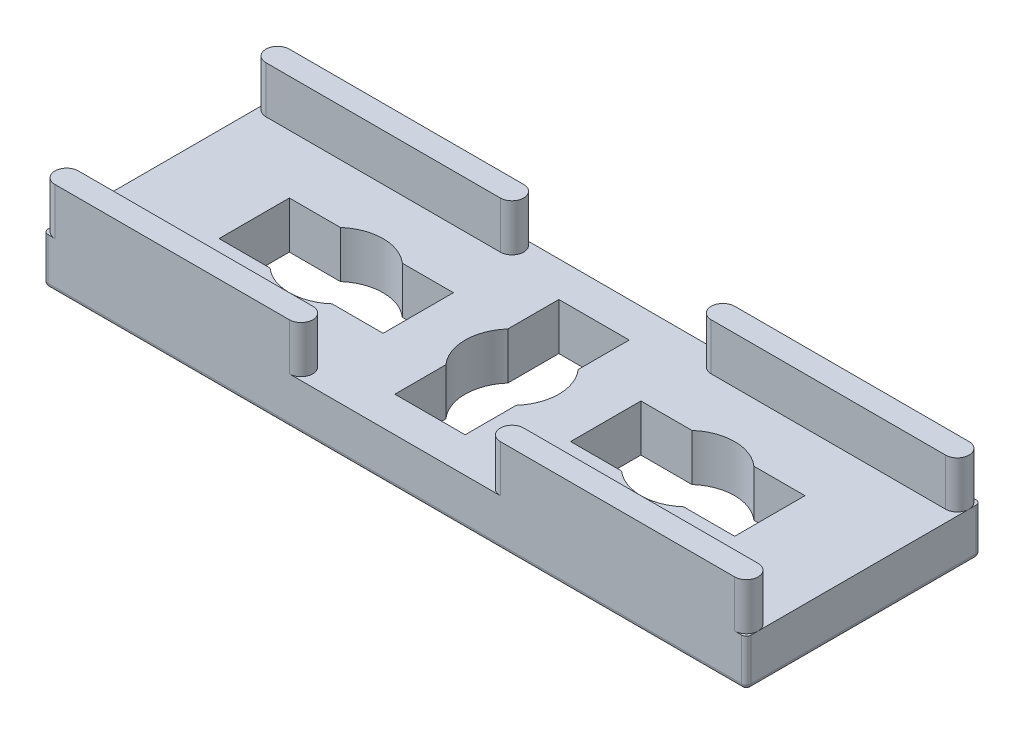
SolidWorks part; units mm, degrees
ref_plane "前视基准面" through (0, 0, 0) normal (0, 0, 1) x (1, 0, 0)
ref_plane "上视基准面" through (0, 0, 0) normal (0, 1, 0) x (1, 0, 0)
ref_plane "右视基准面" through (0, 0, 0) normal (1, 0, 0) x (0, 0, -1)
sketch "草图1" plane through (0, 0, 0) normal (0, 1, 0) x (1, 0, 0)
  line L0 (15, 5) -> (15, -5)
  line L1 (15, 5) -> (-15, 5)
  line L2 (15, -5) -> (-15, -5)
  line L3 (-15, 5) -> (-15, -5)
  line L4 (15, 5) -> (-15, -5) construction
  line L5 (15, -5) -> (-15, 5) construction
  point P1 (0, 0)
  dimension "D1" = 10
  dimension "D2" = 30
extrude "凸台-拉伸1" add sketch "草图1" along normal blind 2
sketch "草图2" plane through (0, 2, 0) normal (0, 1, 0) x (1, 0, 0)
  line L0 (-15, 5) -> (-14.5, 5) construction
  line L1 (15, 5) -> (-15, 5) construction
  line L2 (-14.5, 5) -> (-14.5, 4.5) construction
  line L3 (-14.5, 4.5) -> (-4.5, 4.5) construction
  line L4 (-14.5, 4) -> (-4.5, 4)
  line L5 (-14.5, 5) -> (-4.5, 5)
  arc A0 (-14.5, 5) -> (-14.5, 4) centre (-14.5, 4.5) ccw
  arc A1 (-4.5, 4) -> (-4.5, 5) centre (-4.5, 4.5) ccw
  dimension "D4" = 1
  dimension "D1" = 0.5
  dimension "D2" = 0.5
  dimension "D3" = 10
extrude "凸台-拉伸2" add sketch "草图2" along normal blind 2
mirror "镜向1" about plane through (0, 0, 0) normal (0, 0, 1) of "凸台-拉伸2"
mirror "镜向2" about plane through (0, 0, 0) normal (1, 0, 0) of "凸台-拉伸2", "镜向1"
sketch "草图3" plane through (0, 2, 0) normal (0, 1, 0) x (1, 0, 0)
  line L0 (1.5, -3.5) -> (-1.5, -3.5)
  line L1 (1.5, -3.5) -> (1.5, -1.3229)
  line L2 (-1.5, -3.5) -> (-1.5, -1.3229)
  line L3 (1.5, 3.5) -> (-1.5, 3.5)
  line L4 (1.5, -3.5) -> (-1.5, 3.5) construction
  line L5 (-1.5, -3.5) -> (1.5, 3.5) construction
  line L6 (-1.5, 1.3229) -> (-1.5, 3.5)
  line L7 (1.5, 1.3229) -> (1.5, 3.5)
  arc A0 (-1.5, 1.3229) -> (-1.5, -1.3229) centre (0, 0) ccw
  arc A1 (1.5, -1.3229) -> (1.5, 1.3229) centre (0, 0) ccw
  dimension "D1" = 4
  dimension "D2" = 3
  dimension "D3" = 7
extrude "切除-拉伸1" cut sketch "草图3" against normal up to next
sketch "草图4" plane through (0, 2, 0) normal (0, 1, 0) x (1, 0, 0)
  line L0 (0, 0) -> (-7.5, 0) construction
  line L1 (-4, 1.5) -> (-4, -1.5)
  line L2 (-4, 1.5) -> (-6.1771, 1.5)
  line L3 (-4, -1.5) -> (-6.1771, -1.5)
  line L4 (-11, 1.5) -> (-11, -1.5)
  line L5 (-4, 1.5) -> (-11, -1.5) construction
  line L6 (-4, -1.5) -> (-11, 1.5) construction
  line L7 (-8.8229, 1.5) -> (-11, 1.5)
  line L8 (-8.8229, -1.5) -> (-11, -1.5)
  arc A0 (-8.8229, -1.5) -> (-6.1771, -1.5) centre (-7.5, 0) ccw
  arc A1 (-6.1771, 1.5) -> (-8.8229, 1.5) centre (-7.5, 0) ccw
  dimension "D2" = 4
  dimension "D1" = 7.5
  dimension "D3" = 7
  dimension "D4" = 3
extrude "切除-拉伸2" cut sketch "草图4" against normal up to next
mirror "镜向3" about plane through (0, 0, 0) normal (1, 0, 0) of "切除-拉伸2"
fillet "圆角1" radius 0.2 8 edges at (0, 0, 5) (-15, 1, 5) (-15, 0, 0) (-15, 1, -5) (0, 0, -5) (15, 0, 0) (15, 1, -5) (15, 1, 5)
